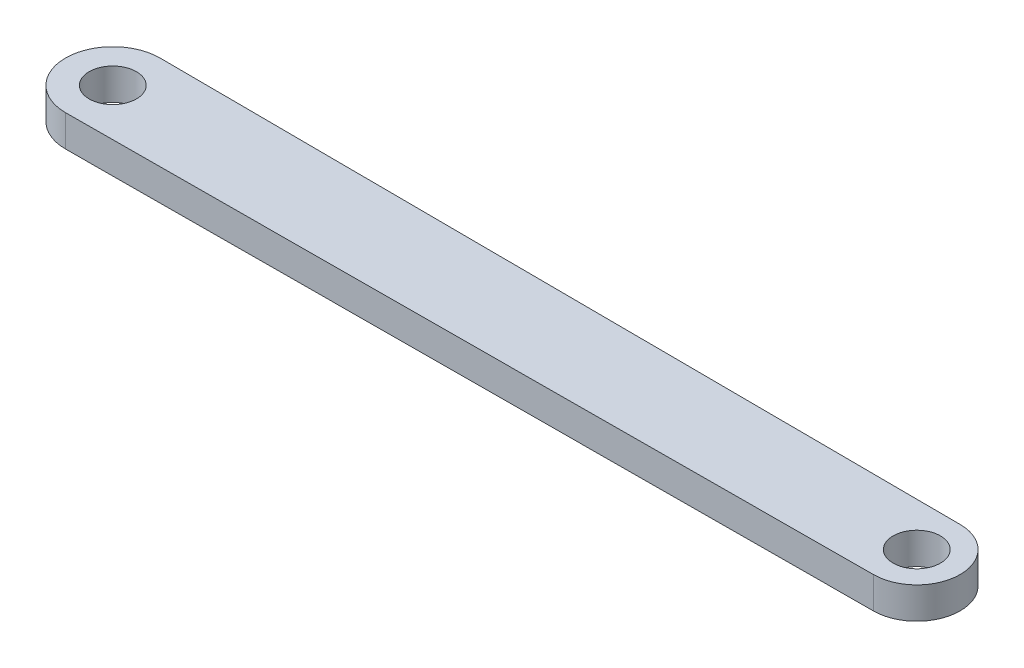
SolidWorks part; units mm, degrees
ref_plane "Front Plane" through (0, 0, 0) normal (0, 0, 1) x (1, 0, 0)
ref_plane "Top Plane" through (0, 0, 0) normal (0, 1, 0) x (1, 0, 0)
ref_plane "Right Plane" through (0, 0, 0) normal (1, 0, 0) x (0, 0, -1)
sketch "Sketch1" plane through (0, 0, 0) normal (0, 1, 0) x (1, 0, 0)
  circle A0 centre (0, 0) radius 1.5
  dimension "D1" = 3
extrude "Boss-Extrude1" add sketch "Sketch1" along normal mid plane 40
sketch "Sketch2" plane through (0, 0, 0) normal (0, 1, 0) x (1, 0, 0)
  line L0 (-29.7739, 0) -> (33.4446, 0) construction
  line L1 (-50.9853, 3) -> (0.0135, 2.75)
  line L2 (-50.9853, -3) -> (0.0135, -2.75)
  arc A2 (0.0135, -2.75) -> (0.0135, 2.75) centre (0, 0) ccw
  arc A3 (-50.9853, 3) -> (-50.9853, -3) centre (-51, 0) ccw
  circle A4 centre (-51, 0) radius 1.5
  dimension "D1" = 5.5
  dimension "D2" = 6
  dimension "D3" = 3
  dimension "D4" = 51
extrude "Boss-Extrude2" add sketch "Sketch2" along normal mid plane 2
sketch "Sketch3" plane through (0, 20, 0) normal (0, 1, 0) x (1, 0, 0)
  circle A1 centre (0, 0) radius 1.5
  circle A2 centre (0, 0) radius 1.5
  dimension "D1" = 0
extrude "Cut-Extrude1" cut sketch "Sketch3" against normal through all
